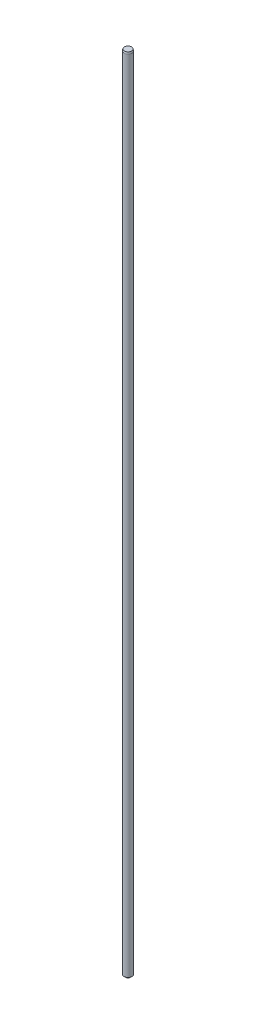
SolidWorks part; units mm, degrees
ref_plane "Plano frontal" through (0, 0, 0) normal (0, 0, 1) x (1, 0, 0)
ref_plane "Plano superior" through (0, 0, 0) normal (0, 1, 0) x (1, 0, 0)
ref_plane "Plano direito" through (0, 0, 0) normal (1, 0, 0) x (0, 0, -1)
ref_plane "Plano1" through (0, 0, 0) normal (0, 0, -1) x (-1, 0, 0)
sketch "Esboço1" plane through (0, 0, 0) normal (0, 0, -1) x (-1, 0, 0)
  line L0 (-6, 0.06) -> (0, 0.06)
  line L1 (0, 0.06) -> (0, 2000.06)
  line L2 (0, 2000.06) -> (-8.9913, 2000.06)
  line L3 (-8.9913, 2000.06) -> (-10, 1996)
  line L4 (-10, 1996) -> (-10, 4.06)
  line L5 (-10, 4.06) -> (-6, 0.06)
  line L6 (0, 0.06) -> (0, 2000.06) construction
  point P6 (0, 0)
  point P7 (-8.9913, 2000.06)
  dimension "D1" = 2000
  dimension "D2" = 10
revolve "Revolução1" add sketch "Esboço1" angle 360 about L6
